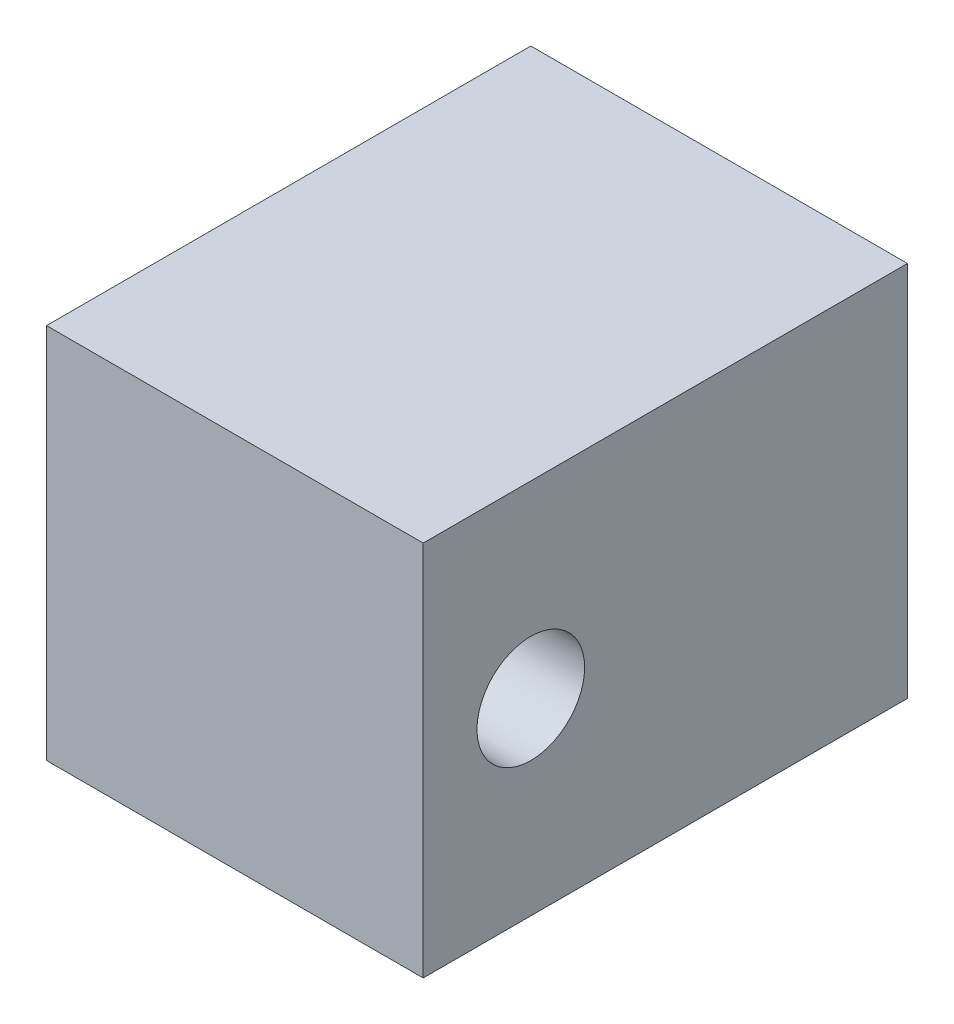
SolidWorks part; units mm, degrees
ref_plane "前视基准面" through (0, 0, 0) normal (0, 0, 1) x (1, 0, 0)
ref_plane "上视基准面" through (0, 0, 0) normal (0, 1, 0) x (1, 0, 0)
ref_plane "右视基准面" through (0, 0, 0) normal (1, 0, 0) x (0, 0, -1)
sketch "草图1" plane through (0, 0, 0) normal (0, 0, 1) x (1, 0, 0)
  line L1 (0, 0) -> (14, 0)
  line L2 (0, 0) -> (0, 14)
  line L3 (0, 14) -> (14, 14)
  line L4 (14, 0) -> (14, 14)
  line L5 (1, 1) -> (13, 1)
  line L6 (1, 1) -> (1, 13)
  line L7 (1, 13) -> (13, 13)
  line L8 (13, 1) -> (13, 13)
  point P5 (1, 1)
extrude "凸台-拉伸1" add sketch "草图1" along normal blind 10
sketch "草图2" plane through (0, 0, 10) normal (0, 0, 1) x (1, 0, 0)
  line L1 (0, 14) -> (14, 14)
  line L2 (0, 14) -> (0, 0)
  line L3 (0, 0) -> (14, 0)
  line L4 (14, 14) -> (14, 0)
extrude "凸台-拉伸2" add sketch "草图2" along normal blind 8
sketch "草图3" plane through (14, 0, 0) normal (1, 0, 0) x (0, 0, -1)
  circle A0 centre (-14, 7) radius 2
  point P0 (-14, 7)
  point P3 (0, 0)
extrude "切除-拉伸1" cut sketch "草图3" against normal blind 14
